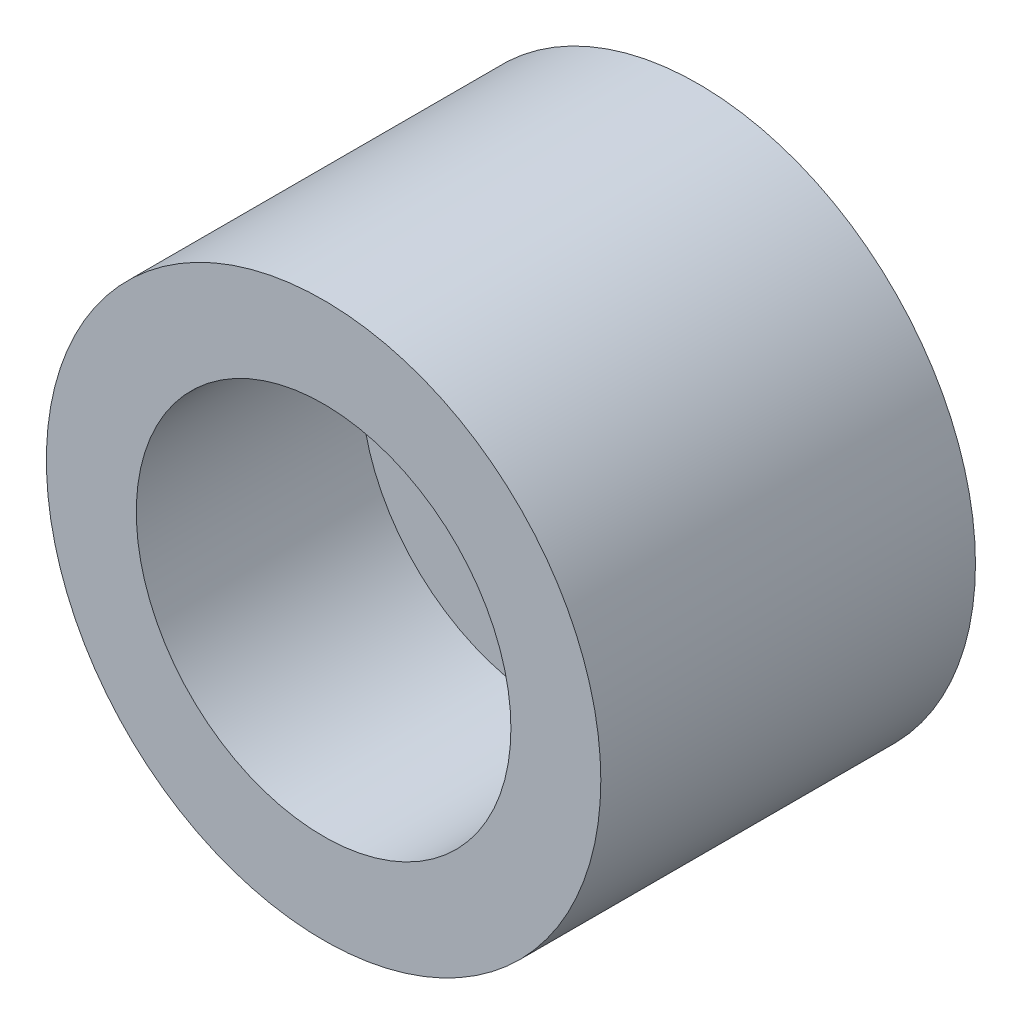
SolidWorks part; units mm, degrees
ref_plane "前视基准面" through (0, 0, 0) normal (0, 0, 1) x (1, 0, 0)
ref_plane "上视基准面" through (0, 0, 0) normal (0, 1, 0) x (1, 0, 0)
ref_plane "右视基准面" through (0, 0, 0) normal (1, 0, 0) x (0, 0, -1)
other "Configuration Table"
sketch "草图1" plane through (0, 0, 0) normal (0, 0, 1) x (1, 0, 0)
  circle A0 centre (0, 0) radius 3.7
extrude "凸台-拉伸1" add sketch "草图1" along normal blind 5
sketch "草图2" plane through (0, 0, 5) normal (0, 0, 1) x (1, 0, 0)
  circle A0 centre (0, 0) radius 2.5
extrude "切除-拉伸1" cut sketch "草图2" against normal blind 3
sketch "草图3" plane through (0, 0, 2) normal (0, 0, 1) x (1, 0, 0)
  circle A0 centre (0, 0) radius 1.5
extrude "切除-拉伸2" cut sketch "草图3" against normal blind 2
